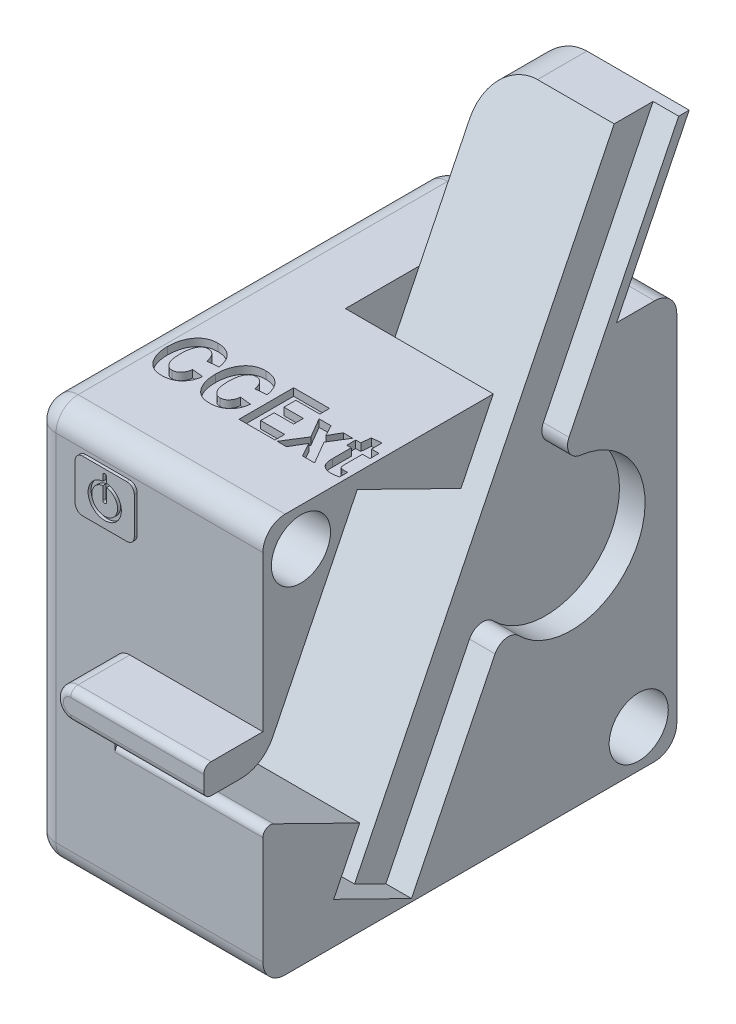
SolidWorks part; units mm, degrees
material "ABS"
ref_plane "Front" through (0, 0, 0) normal (0, 0, 1) x (1, 0, 0)
ref_plane "Top" through (0, 0, 0) normal (0, 1, 0) x (1, 0, 0)
ref_plane "Right" through (0, 0, 0) normal (1, 0, 0) x (0, 0, -1)
sketch "Sketch1" plane through (0, 0, 0) normal (0, 0, 1) x (1, 0, 0)
  line L0 (133.4483, 300.2587) -> (667.2416, 300.2587) construction
  line L2 (-196.85, 342.9) -> (196.85, 342.9)
  line L3 (-196.85, 342.9) -> (-196.85, 0)
  line L4 (-196.85, 0) -> (196.85, 0)
  line L5 (196.85, 342.9) -> (196.85, 0)
  dimension "D1" = 342.9
  dimension "D2" = 393.7
extrude "Boss-Extrude1" add sketch "Sketch1" along normal blind 355.6
sketch "Sketch2" plane through (0, 0, 355.6) normal (0, 0, 1) x (1, 0, 0)
  line L0 (196.85, 342.9) -> (-196.85, 342.9) construction
  line L1 (-158.75, 320.675) -> (-107.95, 320.675)
  line L2 (-158.75, 320.675) -> (-158.75, 276.225)
  line L3 (-158.75, 276.225) -> (-107.95, 276.225)
  line L4 (-107.95, 320.675) -> (-107.95, 276.225)
  line L5 (-158.75, 320.675) -> (-107.95, 276.225) construction
  line L6 (-158.75, 276.225) -> (-107.95, 320.675) construction
  line L7 (-196.85, 342.9) -> (-196.85, 0) construction
  point P0 (-133.35, 298.45)
  dimension "D1" = 44.45
  dimension "D2" = 63.5
  dimension "D3" = 44.45
  dimension "D4" = 50.8
extrude "Boss-Extrude2" add sketch "Sketch2" along normal blind 2.54
sketch "Sketch3" plane through (0, 0, 355.6) normal (0, 0, 1) x (1, 0, 0)
  line L0 (88.9, 298.45) -> (165.1, 298.45) construction
  line L1 (88.9, 307.975) -> (165.1, 307.975)
  line L2 (88.9, 288.925) -> (165.1, 288.925)
  line L5 (-107.95, 298.45) -> (88.9, 298.45) construction
  line L7 (-107.95, 276.225) -> (-107.95, 320.675) construction
  line L8 (196.85, 0) -> (196.85, 342.9) construction
  arc A0 (88.9, 307.975) -> (88.9, 288.925) centre (88.9, 298.45) ccw
  arc A1 (165.1, 288.925) -> (165.1, 307.975) centre (165.1, 298.45) ccw
  point P2 (127, 298.45)
  dimension "D1" = 19.05
  dimension "D2" = 76.2
  dimension "D3" = 31.75
extrude "Boss-Extrude3" add sketch "Sketch3" along normal blind 2.54
sketch "Sketch4" plane through (0, 0, 358.14) normal (0, 0, 1) x (1, 0, 0)
  line L0 (79.375, 298.45) -> (174.625, 298.45) construction
  arc A0 (88.9, 307.975) -> (88.9, 288.925) centre (88.9, 298.45) ccw construction
  arc A1 (165.1, 288.925) -> (165.1, 307.975) centre (165.1, 298.45) ccw construction
  circle A2 centre (92.075, 298.45) radius 3.81
  circle A3 centre (108.2865, 298.45) radius 3.81
  circle A4 centre (124.4979, 298.45) radius 3.81
  dimension "D1" = 7.62
  dimension "D2" = 16.2115
  dimension "D3" = 16.2115
  dimension "D4" = 12.7
extrude "Cut-Extrude1" cut sketch "Sketch4" against normal blind 2.54
sketch "Sketch5" plane through (0, 0, 355.6) normal (0, 0, 1) x (1, 0, 0)
  line L0 (-114.3, 177.8) -> (114.3, 177.8) construction
  line L1 (-114.3, 190.5) -> (114.3, 190.5)
  line L2 (-114.3, 165.1) -> (114.3, 165.1)
  line L3 (0, 177.8) -> (0, 342.9) construction
  line L4 (196.85, 342.9) -> (-196.85, 342.9) construction
  arc A0 (-114.3, 190.5) -> (-114.3, 165.1) centre (-114.3, 177.8) ccw
  arc A1 (114.3, 165.1) -> (114.3, 190.5) centre (114.3, 177.8) ccw
  point P2 (0, 177.8)
  dimension "D1" = 228.6
  dimension "D2" = 25.4
  dimension "D3" = 165.1
extrude "Boss-Extrude4" add sketch "Sketch5" along normal blind 50.8
fillet "Fillet1" radius 6.35 4 edges at (127, 177.8, 406.4) (0, 165.1, 406.4) (-127, 177.8, 406.4) (0, 190.5, 406.4)
fillet "Fillet2" radius 6.35 4 edges at (-158.75, 276.225, 356.87) (-107.95, 276.225, 356.87) (-107.95, 320.675, 356.87) (-158.75, 320.675, 356.87)
sketch "Sketch6" plane through (0, 0, 358.14) normal (0, 0, 1) x (1, 0, 0)
  line L0 (-133.35, 296.545) -> (-133.35, 276.225) construction
  line L3 (-133.35, 296.545) -> (-133.35, 315.595) construction
  line L4 (-134.9375, 296.545) -> (-134.9375, 315.595)
  line L5 (-131.7625, 296.545) -> (-131.7625, 315.595)
  line L6 (-152.4, 276.225) -> (-114.3, 276.225) construction
  circle A1 centre (-133.35, 296.545) radius 11.1125
  circle A2 centre (-133.35, 296.545) radius 14.2875
  arc A3 (-134.9375, 296.545) -> (-131.7625, 296.545) centre (-133.35, 296.545) ccw
  arc A4 (-131.7625, 315.595) -> (-134.9375, 315.595) centre (-133.35, 315.595) ccw
  point P12 (-133.35, 306.07)
  dimension "D2" = 22.225
  dimension "D3" = 3.175
  dimension "D4" = 19.05
  dimension "D5" = 20.32
  dimension "D1" = 3.175
extrude "Cut-Extrude2" cut sketch "Sketch6" against normal blind 2.54 contours L4 A2 L5 A1 | L5 A4 L4 A2 | L5 A2 L4 A1 | L4 A3 L5 A1
fillet "Fillet3" radius 19.05 12 edges at (-196.85, 171.45, 0) (-196.85, 171.45, 355.6) (196.85, 171.45, 0) (196.85, 171.45, 355.6) (0, 0, 0) (0, 0, 355.6) (0, 342.9, 0) (0, 342.9, 355.6) (-196.85, 342.9, 177.8) (196.85, 0, 177.8) (-196.85, 0, 177.8) (196.85, 342.9, 177.8)
sketch "Sketch7" plane through (0, 0, 0) normal (1, 0, 0) x (0, 0, -1)
  line L0 (-51.7276, 342.9) -> (10.6627, 469.9)
  line L1 (-336.55, 342.9) -> (-19.05, 342.9) construction
  line L2 (-94.1768, 342.9) -> (-31.7865, 469.9)
  line L3 (-31.7865, 469.9) -> (10.6627, 469.9)
  line L4 (-94.1768, 342.9) -> (-51.7276, 342.9)
  line L5 (0, 323.85) -> (0, 19.05) construction
  dimension "D1" = 38.1
  dimension "D2" = 127
  dimension "D3" = 94.1768
  dimension "D4" = 63.837
extrude "Boss-Extrude5" add sketch "Sketch7" along normal mid plane 254
fillet "Fillet4" radius 39.116 2 edges at (-127, 469.9, 10.5619) (127, 469.9, 10.5619)
sketch "Sketch8" plane through (0, 342.9, 0) normal (0, 1, 0) x (1, 0, 0)
  line L0 (0, -94.1768) -> (0, -125.9268) construction
  line L1 (127, -94.1768) -> (-127, -94.1768) construction
  line L3 (-127, -157.6768) -> (127, -157.6768)
  line L4 (-127, -157.6768) -> (-127, -94.1768)
  line L5 (-127, -94.1768) -> (127, -94.1768)
  line L6 (127, -157.6768) -> (127, -94.1768)
  line L7 (-127, -157.6768) -> (127, -94.1768) construction
  line L8 (-127, -94.1768) -> (127, -157.6768) construction
  dimension "D1" = 63.5
  dimension "D2" = 254
extrude "Cut-Extrude3" cut sketch "Sketch8" against normal blind 25.4
sketch "Sketch9" plane through (0, 0, 0) normal (1, 0, 0) x (0, 0, -1)
  line L1 (-912.7094, 769.4471) -> (-210.006, -1175.153)
  line L2 (-210.006, -1175.153) -> (1122.7154, 405.706)
  line L3 (1122.7154, 405.706) -> (-912.7094, 769.4471)
  circle A0 centre (0, 0) radius 596.8851 construction
extrude "Cut-Extrude4" cut sketch "Sketch9" along normal through all
sketch "Sketch10" plane through (0, 0, 0) normal (1, 0, 0) x (0, 0, -1)
  line L0 (-94.1768, 342.9) -> (-254.8643, 15.8091)
  line L1 (-157.6768, 342.9) -> (-185.414, 286.439)
  line L2 (-31.7865, 469.9) -> (-94.1768, 342.9) construction
  line L3 (-355.6, 165.1) -> (-274.4926, 330.2)
  line L5 (-355.6, 19.05) -> (-355.6, 165.1) construction
  line L7 (-355.6, 165.1) -> (-355.6, 121.8957)
  line L9 (-157.6768, 342.9) -> (-94.1768, 342.9)
  line L14 (-274.4926, 330.2) -> (-185.414, 286.439)
  line L15 (-355.6, 121.8957) -> (-268.5142, 299.1651) construction
  line L16 (-157.6768, 342.9) -> (-336.55, 342.9) construction
  line L17 (-355.6, 121.8957) -> (-272.3609, 81.0035)
  line L19 (-254.8643, 15.8091) -> (-294.7601, 35.4084)
  line L20 (-294.7601, 35.4084) -> (-272.3609, 81.0035)
  dimension "D1" = 19.05
  dimension "D2" = 12.7
  dimension "D3" = 50.8
  dimension "D4" = 44.45
extrude "Cut-Extrude5" cut sketch "Sketch10" against normal blind 127
sketch "Sketch11" plane through (0, 0, 0) normal (1, 0, 0) x (0, 0, -1)
  line L0 (-94.1768, 342.9) -> (-106.6549, 317.5)
  line L1 (-106.6549, 317.5) -> (-94.1768, 317.5)
  line L2 (-94.1768, 317.5) -> (-94.1768, 342.9)
extrude "Boss-Extrude6" add sketch "Sketch11" against normal up to surface (127 mm away) up to face at (-127, 214.2414, 222.3434)
sketch "Sketch12" plane through (0, 103.9367, 211.5706) normal (0, 0.4409, 0.8975) x (1, 0, 0)
  line L0 (-127, -98.1877) -> (0, -98.1877) construction
  line L1 (0, 426.4566) -> (-22, 426.4566)
  line L2 (0, 426.4566) -> (0, -98.1877)
  line L3 (0, -98.1877) -> (-22, -98.1877)
  line L4 (-22, 426.4566) -> (-22, -98.1877)
  dimension "D1" = 22
extrude "Cut-Extrude6" cut sketch "Sketch12" against normal blind 30
sketch "Sketch13" plane through (0, 0, 0) normal (1, 0, 0) x (0, 0, -1)
  line L0 (-90.7362, 196.8695) -> (0, 196.8695) construction
  line L1 (0, 19.05) -> (0, 323.85) construction
  line L2 (-90.7362, 196.8695) -> (-90.7362, 0) construction
  line L3 (-336.55, 0) -> (-19.05, 0) construction
  circle A0 centre (-90.7362, 196.8695) radius 63.5
  dimension "D3" = 127
  dimension "D1" = 196.8695
  dimension "D2" = 90.7362
extrude "Cut-Extrude7" cut sketch "Sketch13" against normal up to surface (22 mm away) up to face at (-22, 239.5476, 128.2377)
fillet "Fillet5" radius 12.7 2 edges at (-11, 167.3852, 146.9761) (-11, 259.4033, 101.771)
sketch "Sketch14" plane through (0, 0, 0) normal (1, 0, 0) x (0, 0, -1)
  line L0 (-400.05, 165.1) -> (-355.6, 165.1) construction
  line L1 (-274.4926, 330.2) -> (-355.6, 165.1) construction
  line L2 (-274.4926, 330.2) -> (-355.6, 165.1) construction
  line L3 (-374.5857, 165.1) -> (-355.6, 165.1)
  line L4 (-355.6, 165.1) -> (-347.2286, 182.1405)
  arc A0 (-374.5857, 165.1) -> (-347.2286, 182.1405) centre (-374.5857, 195.58) ccw
  dimension "D1" = 30.48
extrude "Cut-Extrude8" cut sketch "Sketch14" against normal up to surface (127 mm away) up to face at (-127, 191.2951, 249.4384)
fillet "Fillet7" radius 6.35 1 edges at (-63.5, 121.8957, 355.6)
sketch "Sketch15" plane through (0, 0, 0) normal (1, 0, 0) x (0, 0, -1)
  circle A0 centre (-322.9044, 310.2044) radius 25.4
  circle A1 centre (-32.6956, 32.6956) radius 25.4
  dimension "D1" = 50.8
  dimension "D2" = 50.8
extrude "Cut-Extrude9" cut sketch "Sketch15" against normal blind 53.34
sketch "Sketch16" plane through (0, 342.9, 0) normal (0, 1, 0) x (1, 0, 0)
  line L0 (-177.8, -336.55) -> (-177.8, -285.75) construction
  text T0 "CCExtractor" font "Franklin Gothic Medium" height in points 190
  point P2 (-166.1897, -355.6)
  point P3 (-177.8, -336.55)
  point P4 (-167.973, -355.6)
  point P6 (0, 0)
  point P7 (70.9867, -315.8624)
  point P9 (60.8814, -62.6365)
  point P10 (-177.8, -289.7076)
  dimension "D1" = 50.8
extrude "Cut-Extrude10" cut sketch "Sketch16" against normal blind 6.35
equation "\"D3@Sketch4\"=\"D2@Sketch4\""
